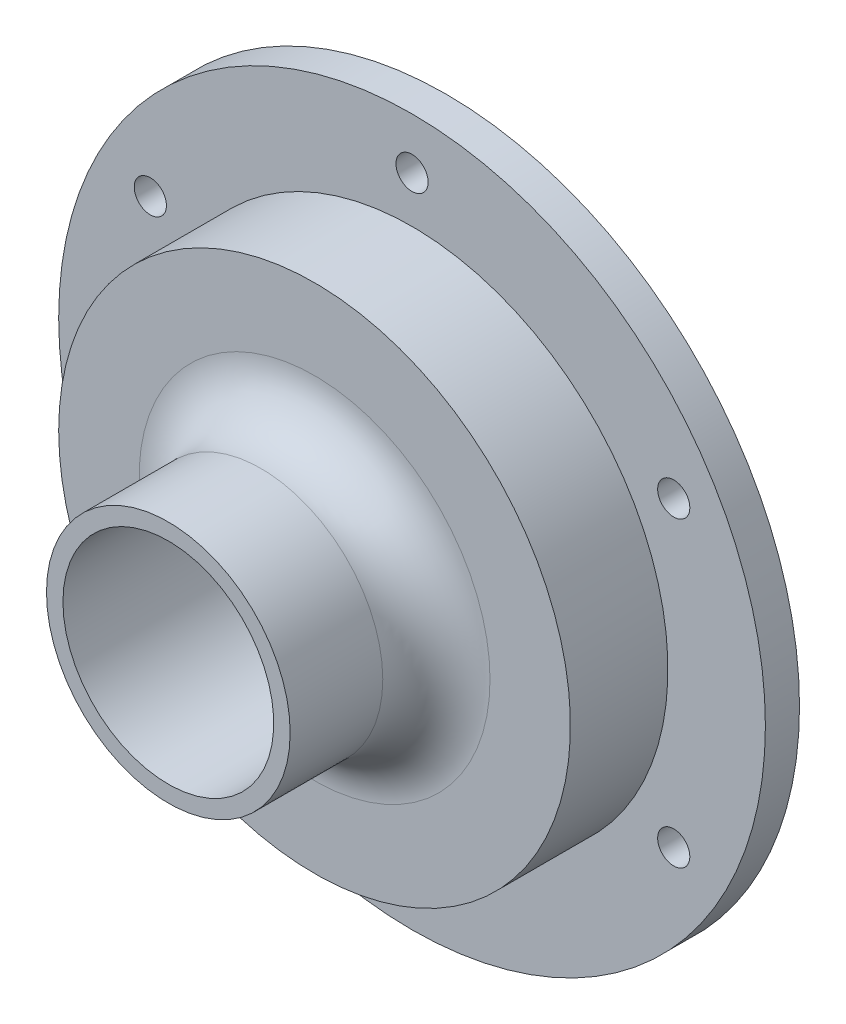
SolidWorks part; units mm, degrees
ref_plane "Front Plane" through (0, 0, 0) normal (0, 0, 1) x (1, 0, 0)
ref_plane "Top Plane" through (0, 0, 0) normal (0, 1, 0) x (1, 0, 0)
ref_plane "Right Plane" through (0, 0, 0) normal (1, 0, 0) x (0, 0, -1)
sketch "Sketch2" plane through (0, 0, 0) normal (0, 1, 0) x (1, 0, 0)
  line L0 (-72.5, 0) -> (72.5, 0) construction
  line L1 (-72.5, 0) -> (-72.5, -7)
  line L2 (-72.5, -7) -> (-52.5, -7)
  line L3 (-52.5, -7) -> (-52.5, -27)
  line L4 (-52.5, -27) -> (-25, -27)
  line L5 (-25, -27) -> (-25, -57)
  line L6 (-25, -57) -> (-21.625, -57)
  line L7 (-21.625, -57) -> (-21.625, 0)
  line L8 (-21.625, 0) -> (-72.5, 0)
  line L9 (0, 0) -> (0, -58.4993) construction
  dimension "D1" = 145
  dimension "D2" = 21.625
  dimension "D3" = 25
  dimension "D4" = 20
  dimension "D5" = 7
  dimension "D6" = 30
  dimension "D7" = 20
revolve "Revolve1" add sketch "Sketch2" angle 360 about L9
fillet "Fillet1" radius 11 1 edges at (-25, 0, 27)
sketch "Sketch5" plane through (0, 0, 0) normal (0, 0, -1) x (-1, 0, 0)
  point P0 (0, 62)
  dimension "D1" = 62
hole_wizard "CBORE for M6 Hex Head Bolt1" positions "Sketch5" profile "Sketch4" counterbore size "M6" standard "ISO" end condition through all
sketch "Sketch4" plane through (0, 62, 0) normal (1, 0, 0) x (0, 1, 0)
  line L0 (0, 0) -> (0, 57)
  line L1 (0, 57) -> (3.3, 57)
  line L3 (3.3, 57) -> (3.3, 1)
  line L4 (3.3, 1) -> (7.2735, 1)
  line L5 (7.2735, 1) -> (7.2735, 0)
  line L7 (7.2735, 0) -> (0, 0)
  line L11 (0, -6.35) -> (0, 107.95) construction
  dimension "Thru Hole Dia." = 6.6
  dimension "Thru Hole Depth" = 57
  dimension "C'Bore Dia." = 14.547
  dimension "C'Bore Depth" = 1
pattern_circular "CirPattern1" count 6 over 360 about axis through (0, 0, 0) along (0, 0, 1) of "CBORE for M6 Hex Head Bolt1"
